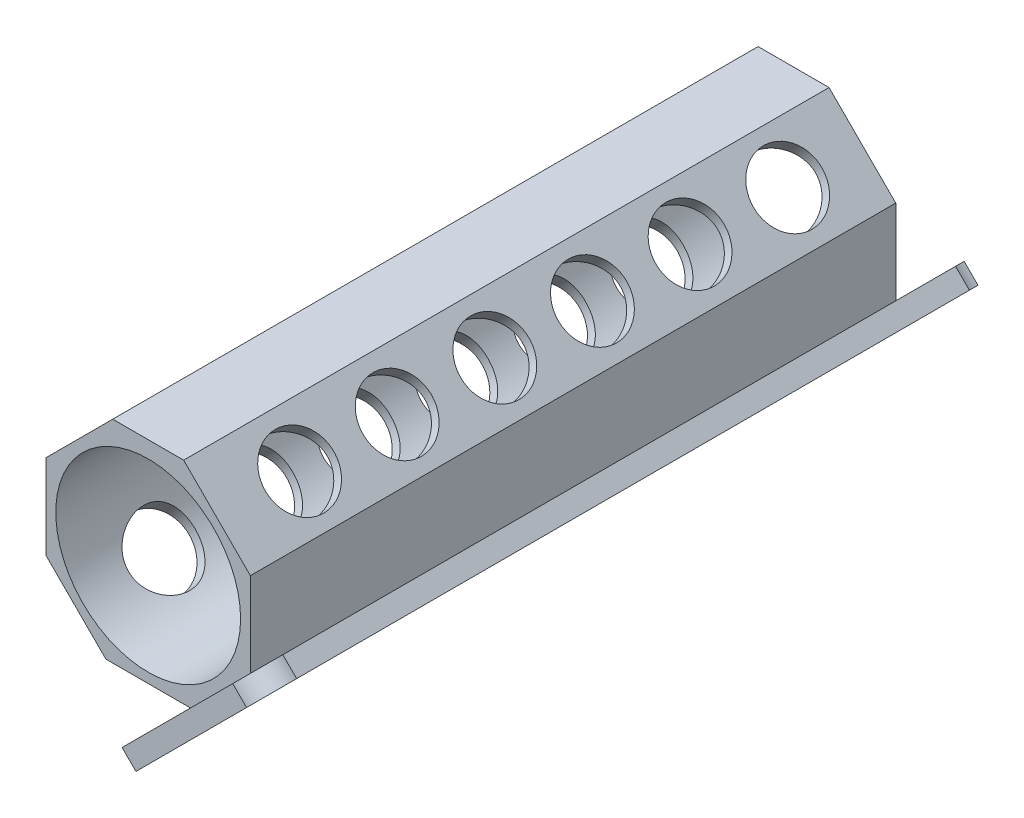
SolidWorks part; units mm, degrees
ref_plane "Ebene vorne" through (0, 0, 0) normal (1, 0, 0) x (0, 1, 0)
ref_plane "Ebene oben" through (0, 0, 0) normal (0, 0, 1) x (0, 1, 0)
ref_plane "Ebene rechts" through (0, 0, 0) normal (0, 1, 0) x (-1, 0, 0)
sketch "Skizze1" plane through (0, 0, 0) normal (0, 0, 1) x (0, 1, 0)
  line L0 (11.1508, 3.6277) -> (11.1508, -3.6277)
  line L13 (11.1508, 3.6277) -> (4.3285, 10.45)
  line L14 (4.3285, 10.45) -> (-4.3285, 10.45)
  line L15 (-4.3285, 10.45) -> (-10.45, 4.3285)
  line L16 (-10.45, 4.3285) -> (-10.45, -4.3285)
  line L17 (-10.45, -4.3285) -> (-4.3285, -10.45)
  line L18 (-4.3285, -10.45) -> (4.3285, -10.45)
  line L19 (4.3285, -10.45) -> (11.1508, -3.6277)
  line L29 (10.45, -2.605) -> (10.45, 5.6378) [skipped]
  circle A0 centre (0, 0) radius 9.45
  circle A1 centre (0, 0) radius 10.45 construction
  dimension "D1" = 18.9
  dimension "D2" = 20.9
extrude "Aufsatz-Linear austragen1" add sketch "Skizze1" along normal blind 66
sketch "Skizze9" plane through (7.3893, 7.3893, 0) normal (0.7071, 0.7071, 0) x (-0.7071, 0.7071, 0)
  line L0 (0.4955, 66) -> (0, 0) construction
  line L1 (-4.3285, 66) -> (5.3196, 66) construction
  circle A0 centre (0.4325, 57.6) radius 3.5
  circle A1 centre (0.4566, 47.6) radius 3.5
  circle A2 centre (0.4807, 37.6001) radius 3.5
  circle A3 centre (0.5048, 27.6001) radius 3.5
  circle A4 centre (0.5289, 17.6001) radius 3.5
  circle A5 centre (0.553, 7.6001) radius 3.5
  dimension "D1" = 7
  dimension "D2" = 8.4
  dimension "D3" = 6
extrude "Schnitt-Linear austragen8" cut sketch "Skizze9" against normal through all
sketch "Skizze13" plane through (7.3893, -7.3893, 0) normal (0.7071, -0.7071, 0) x (0.7071, 0.7071, 0)
  line L0 (0, 66) -> (0, 0) construction
  line L1 (-11, -4.4) -> (11, -4.4)
  line L2 (-11, -4.4) -> (-11, 70.4)
  line L3 (-11, 70.4) -> (11, 70.4)
  line L4 (11, -4.4) -> (11, 70.4)
  line L5 (-11, -4.4) -> (11, 70.4) construction
  line L6 (-11, 70.4) -> (11, -4.4) construction
  line L7 (-4.3285, 66) -> (4.3285, 66) construction
  point P0 (0, 33)
  point P10 (0, 0)
  point P11 (0, 33)
  dimension "D1" = 22
  dimension "D2" = 74.8
extrude "Aufsatz-Linear austragen2" add sketch "Skizze13" along normal blind 2
sketch "Skizze14" plane through (8.8035, -8.8035, 0) normal (0.7071, -0.7071, 0) x (0.7071, 0.7071, 0)
  circle A0 centre (11, 70.4) radius 3
  circle A1 centre (-11, 70.4) radius 3
  circle A2 centre (-11, -4.4) radius 3
  circle A3 centre (11, -4.4) radius 3
  dimension "D1" = 6
  dimension "D2" = 6
  dimension "D3" = 6
  dimension "D4" = 6
extrude "Schnitt-Linear austragen12" cut sketch "Skizze14" against normal blind 2
